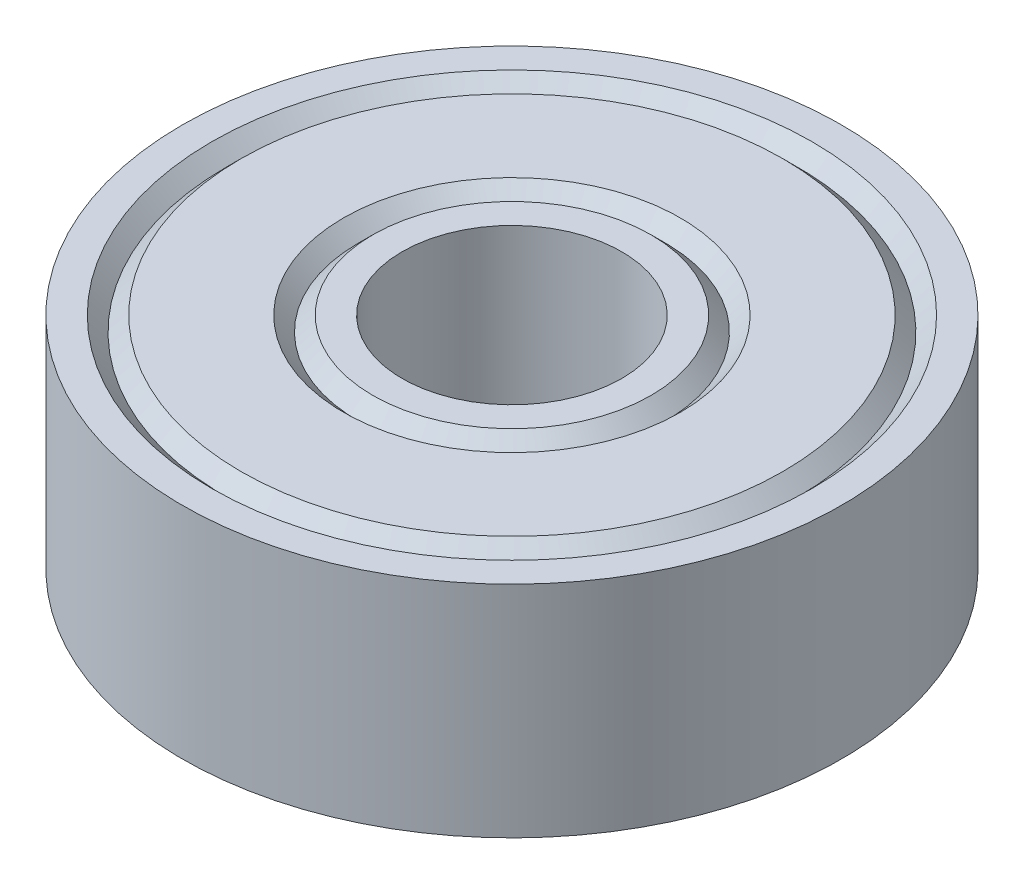
SolidWorks part; units mm, degrees
ref_plane "Front Plane" through (0, 0, 0) normal (0, 0, 1) x (1, 0, 0)
ref_plane "Top Plane" through (0, 0, 0) normal (0, 1, 0) x (1, 0, 0)
ref_plane "Right Plane" through (0, 0, 0) normal (1, 0, 0) x (0, 0, -1)
sketch "Sketch1" plane through (0, 0, 0) normal (0, 0, 1) x (1, 0, 0)
  line L0 (0, 2) -> (0, -2) construction
  line L1 (-2, 2) -> (-2.5333, 2)
  line L2 (-2, 2) -> (-2, -2)
  line L3 (-2, -2) -> (-2.5333, -2)
  line L4 (-6, 2) -> (-6, -2)
  line L5 (-5.4667, 2) -> (-5.2, 1.7333)
  line L6 (-5.2, 1.7333) -> (-4.9333, 2)
  line L7 (-3.0667, 2) -> (-2.8, 1.7333)
  line L8 (-2.8, 1.7333) -> (-2.5333, 2)
  line L9 (-5.4667, -2) -> (-5.2, -1.7333)
  line L10 (-5.2, -1.7333) -> (-4.9333, -2)
  line L11 (-3.0667, -2) -> (-2.8, -1.7333)
  line L12 (-2.8, -1.7333) -> (-2.5333, -2)
  line L13 (-3.0667, -2) -> (-4.9333, -2)
  line L14 (-5.4667, -2) -> (-6, -2)
  line L15 (-5.4667, 2) -> (-6, 2)
  line L16 (-3.0667, 2) -> (-4.9333, 2)
  line L17 (-5.2, 1.7333) -> (-2.8, 1.7333) construction
  line L18 (-5.2, 1.7333) -> (-5.2, -1.7333) construction
  line L19 (-2.8, -1.7333) -> (-5.2, -1.7333) construction
  line L20 (-2.8, 1.7333) -> (-2.8, -1.7333) construction
  line L21 (-5.2, 0) -> (-4.4, 0) construction
  line L22 (-2.5333, 2) -> (-3.0667, 2) construction
  line L23 (-4.4, 0) -> (-3.6, 0) construction
  line L24 (-5.2, 0) -> (-6, 0) construction
  line L25 (-3.6, 0) -> (-2.8, 0) construction
  line L26 (-2.8, 0) -> (-2, 0) construction
  dimension "D1" = 4
  dimension "D2" = 4
  dimension "D3" = 12
revolve "Revolve1" add sketch "Sketch1" angle 360 about L0
